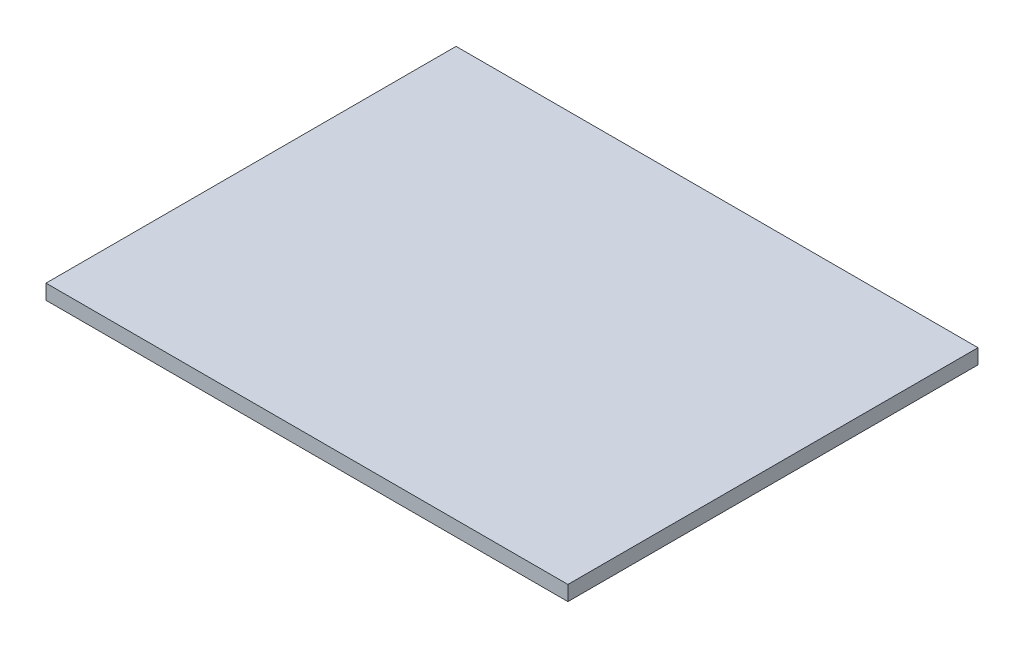
SolidWorks part; units mm, degrees
ref_plane "Front Plane" through (0, 0, 0) normal (0, 0, 1) x (1, 0, 0)
ref_plane "Top Plane" through (0, 0, 0) normal (0, 1, 0) x (1, 0, 0)
ref_plane "Right Plane" through (0, 0, 0) normal (1, 0, 0) x (0, 0, -1)
sketch "Sketch1" plane through (0, 0, 0) normal (0, 1, 0) x (1, 0, 0)
  line L0 (0, 38.9292) -> (0, -47.5136) construction
  line L1 (-35, 27.5) -> (35, 27.5)
  line L2 (-35, 27.5) -> (-35, -27.5)
  line L3 (-35, -27.5) -> (35, -27.5)
  line L4 (35, 27.5) -> (35, -27.5)
  line L5 (-39.8276, 0) -> (38.2305, 0) construction
  dimension "D1" = 55
  dimension "D2" = 70
  dimension "D3" = 35
  dimension "D4" = 27.5
extrude "Boss-Extrude1" add sketch "Sketch1" along normal blind 2
